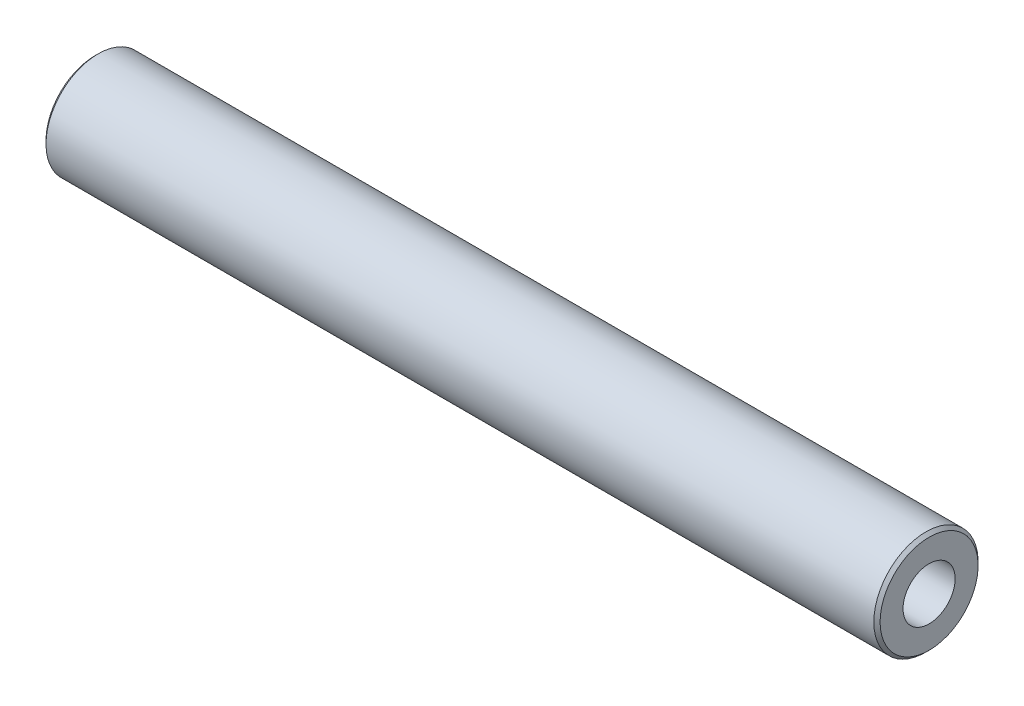
SolidWorks part; units mm, degrees
material "镀铬光轴"
ref_plane "前视" through (0, 0, 0) normal (0, 0, 1) x (1, 0, 0)
ref_plane "上视" through (0, 0, 0) normal (0, 1, 0) x (1, 0, 0)
ref_plane "右视" through (0, 0, 0) normal (1, 0, 0) x (0, 0, -1)
sketch "草图1" plane through (0, 0, 0) normal (0, 1, 0) x (1, 0, 0)
  line L0 (-1000, 0) -> (49000, 0) construction
  line L1 (0, 0) -> (0, 5)
  line L6 (0, 5) -> (80, 5)
  line L11 (80, 5) -> (80, 0)
  line L12 (80, 0) -> (0, 0)
  dimension "D1" = 10
  dimension "D5" = 80
revolve "旋转1" add sketch "草图1" angle 360 about L0
hole_wizard "M6 螺纹孔1" positions "草图3" profile "草图2" tap size "M6" standard "Gb"
sketch "草图3" plane through (80, 0, 0) normal (1, 0, 0) x (0, 0, -1)
  point P0 (0, 0)
sketch "草图2" plane through (80, 0, 0) normal (0, 1, 0) x (0, 0, -1)
  line L0 (0, 0) -> (0, 16.5022)
  line L1 (0, 16.5022) -> (2.5, 15)
  line L2 (2.5, 15) -> (2.5, 0)
  line L5 (2.5, 0) -> (0, 0)
  line L10 (0, 16.5022) -> (-2.5, 15) construction
  line L11 (0, -6.35) -> (0, 107.95) construction
  dimension "螺纹孔钻头直径" = 5
  dimension "螺纹孔钻头深度" = 15
  dimension "导头角度" = 118
cosmetic thread "孔螺蚊线1" parameters "D1"=12, "D2"=6
hole_wizard "M6 螺纹孔2" positions "草图5" profile "草图4" tap size "M6" standard "Gb"
sketch "草图5" plane through (0, 0, 0) normal (-1, 0, 0) x (0, 0, 1)
  point P0 (0, 0)
sketch "草图4" plane through (0, 0, 0) normal (0, 1, 0) x (0, 0, 1)
  line L0 (0, 0) -> (0, 16.5022)
  line L1 (0, 16.5022) -> (2.5, 15)
  line L2 (2.5, 15) -> (2.5, 0)
  line L5 (2.5, 0) -> (0, 0)
  line L10 (0, 16.5022) -> (-2.5, 15) construction
  line L11 (0, -6.35) -> (0, 107.95) construction
  dimension "螺纹孔钻头直径" = 5
  dimension "螺纹孔钻头深度" = 15
  dimension "导头角度" = 118
cosmetic thread "孔螺蚊线2" parameters "D1"=12, "D2"=6
chamfer "倒角1" distance 0.3 angle 45 2 edges at (80, 0, 5) (0, 0, 5)
